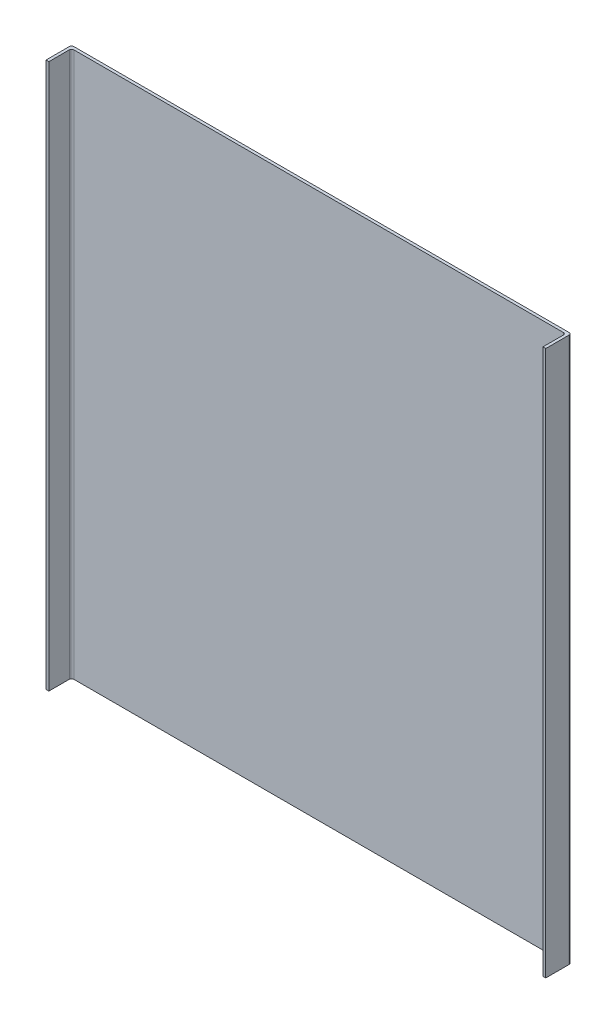
SolidWorks part; units mm, degrees
ref_plane "Front Plane" through (0, 0, 0) normal (0, 0, 1) x (1, 0, 0)
ref_plane "Top Plane" through (0, 0, 0) normal (0, 1, 0) x (1, 0, 0)
ref_plane "Right Plane" through (0, 0, 0) normal (1, 0, 0) x (0, 0, -1)
sketch "Sketch1" plane through (0, 0, 0) normal (0, 0, 1) x (1, 0, 0)
  line L1 (0, 0) -> (1117.6, 0)
  line L2 (0, 0) -> (0, 1219.2)
  line L3 (0, 1219.2) -> (1117.6, 1219.2)
  line L4 (1117.6, 0) -> (1117.6, 1219.2)
  dimension "D1" = 1117.6
  dimension "D2" = 1219.2
extrude "Boss-Extrude1" add sketch "Sketch1" along normal blind 6.35 contours L3 L4 L1 L2
sketch "Sketch2" plane through (0, 0, 6.35) normal (0, 0, 1) x (1, 0, 0)
  line L0 (0, 0) -> (1117.6, 0) construction
  line L1 (0, 1219.2) -> (6.35, 1219.2)
  line L2 (0, 1219.2) -> (0, 0)
  line L3 (0, 0) -> (6.35, 0)
  line L4 (6.35, 1219.2) -> (6.35, 0)
  line L6 (1117.6, 1219.2) -> (1111.25, 1219.2)
  line L7 (1117.6, 1219.2) -> (1117.6, 0)
  line L8 (1117.6, 0) -> (1111.25, 0)
  line L9 (1111.25, 1219.2) -> (1111.25, 0)
  dimension "D1" = 6.35
extrude "Boss-Extrude2" add sketch "Sketch2" along normal blind 50.8
fillet "Fillet1" radius 5 4 edges at (1117.6, 609.6, 0) (0, 609.6, 0) (1111.25, 609.6, 6.35) (6.35, 609.6, 6.35)
